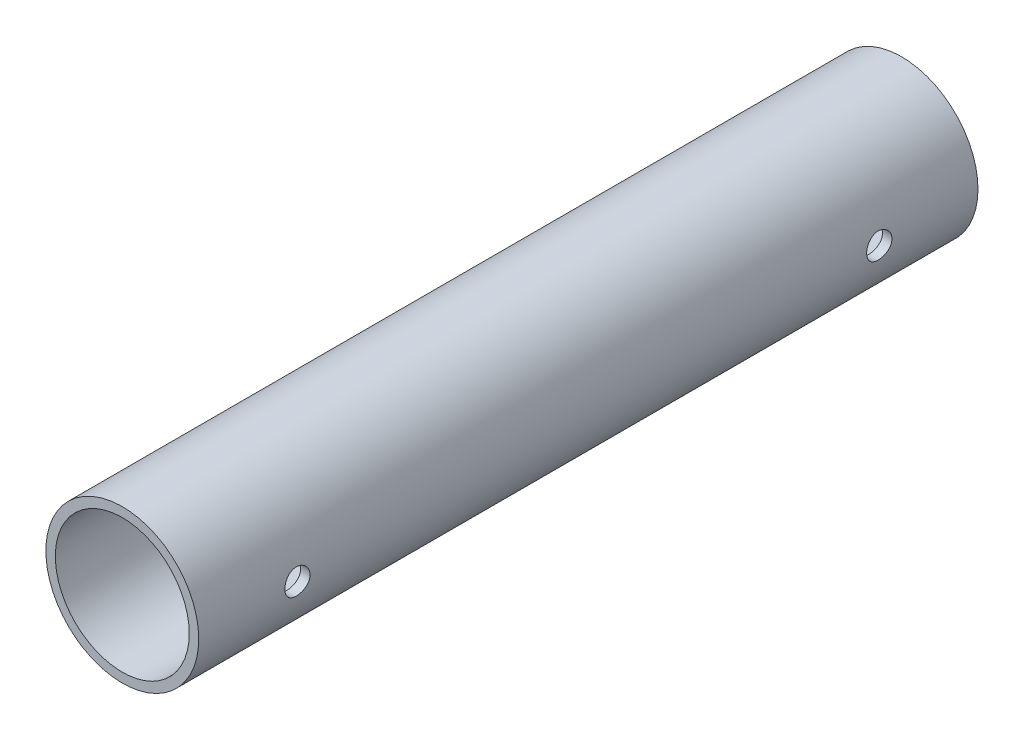
SolidWorks part; units mm, degrees
ref_plane "Front Plane" through (0, 0, 0) normal (0, 0, 1) x (1, 0, 0)
ref_plane "Top Plane" through (0, 0, 0) normal (0, 1, 0) x (1, 0, 0)
ref_plane "Right Plane" through (0, 0, 0) normal (1, 0, 0) x (0, 0, -1)
sketch "Sketch1" plane through (0, 0, 0) normal (0, 0, 1) x (1, 0, 0)
  circle A0 centre (0, 0) radius 10.6
  circle A1 centre (0, 0) radius 12.1
  dimension "D1" = 24.2
  dimension "D2" = 1.5
extrude "Boss-Extrude1" add sketch "Sketch1" along normal blind 61.68
sketch "Sketch2" plane through (0, 0, 0) normal (1, 0, 0) x (0, 0, -1)
  line L0 (-61.68, 12.1) -> (-61.68, -12.1) construction
  circle A0 centre (-46.055, 0) radius 2
  dimension "D1" = 4
  dimension "D2" = 15.625
extrude "Cut-Extrude1" cut sketch "Sketch2" against normal through all both and the other way through all
mirror "Mirror1" about plane through (0, 0, 0) normal (0, 0, 1) of "Boss-Extrude1", "Cut-Extrude1"
